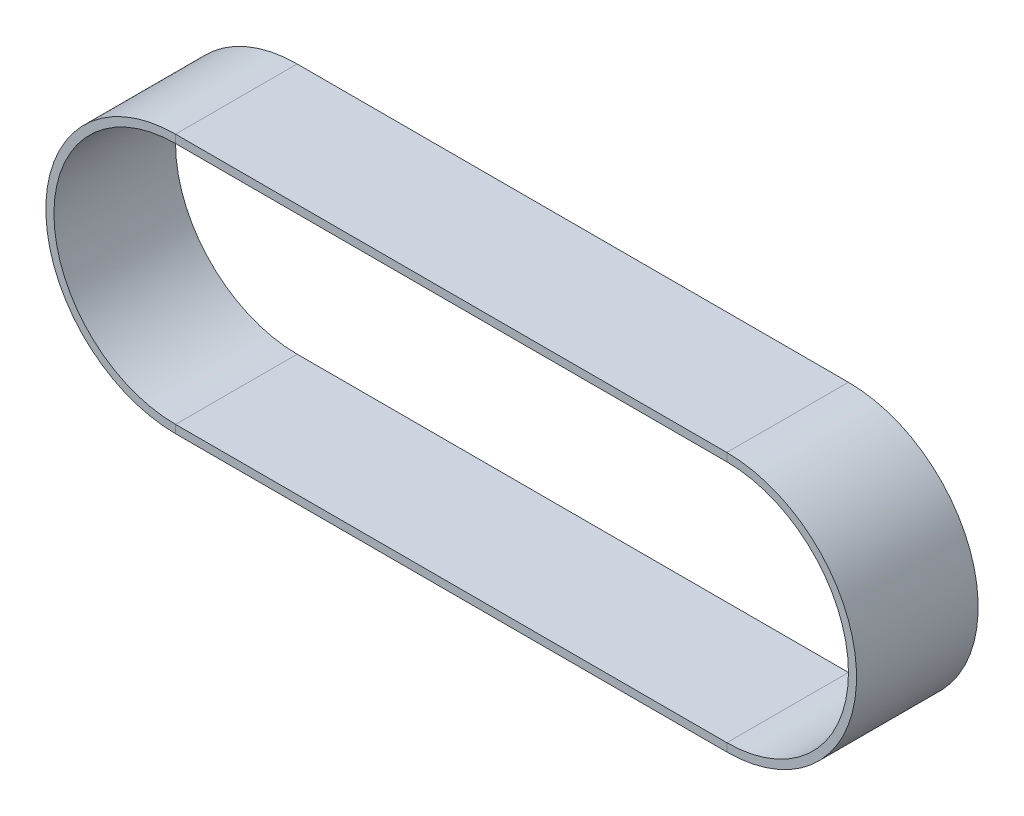
SolidWorks part; units mm, degrees
material "EPDM 60 Durometer"
ref_plane "Ebene vorne" through (0, 0, 0) normal (0, 0, 1) x (1, 0, 0)
ref_plane "Ebene oben" through (0, 0, 0) normal (0, 1, 0) x (1, 0, 0)
ref_plane "Ebene rechts" through (0, 0, 0) normal (1, 0, 0) x (0, 0, -1)
sketch "Skizze2" plane through (0, 0, 0) normal (0, 0, 1) x (1, 0, 0)
  line L0 (0, 0) -> (1, 0) construction
  line L1 (0, 0) -> (0, 1) construction
  line L2 (0, -300) -> (-1360, -300)
  line L3 (-1360, 300) -> (0, 300)
  arc A0 (0, 300) -> (0, -300) centre (0, 0) cw
  arc A1 (-1360, -300) -> (-1360, 300) centre (-1360, 0) cw
sketch3d "3D-Skizze1"
  line L0 (-1360, 300, 0) -> (0, 300, 0) construction
  line L2 (0, 320, 150) -> (0, 320, -150)
  line L3 (0, 320, 150) -> (0, 300, 150)
  line L4 (0, 300, 150) -> (0, 300, -150)
  line L5 (0, 320, -150) -> (0, 300, -150)
  point P7 (0, 300, 0)
  dimension "D1" = 300
  dimension "D2" = 20
sweep "Austragung1" add profiles "3D-Skizze1" path "Skizze2"
